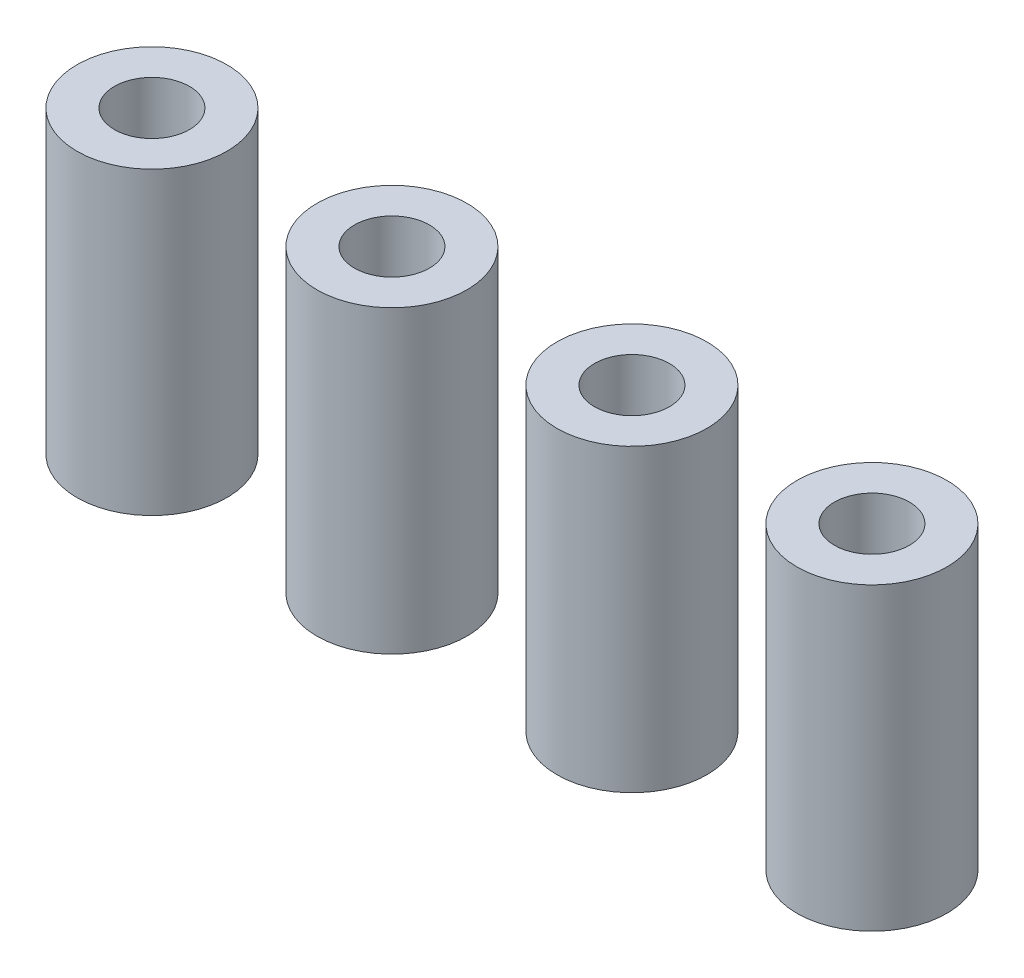
SolidWorks part; units mm, degrees
ref_plane "Front Plane" through (0, 0, 0) normal (0, 0, 1) x (1, 0, 0)
ref_plane "Top Plane" through (0, 0, 0) normal (0, 1, 0) x (1, 0, 0)
ref_plane "Right Plane" through (0, 0, 0) normal (1, 0, 0) x (0, 0, -1)
sketch "Sketch1" plane through (0, 0, 0) normal (0, 1, 0) x (1, 0, 0)
  circle A0 centre (0, 0) radius 2.5
  circle A1 centre (0, 0) radius 1.25
  circle A2 centre (8, 0) radius 2.5
  circle A3 centre (8, 0) radius 1.25
  circle A4 centre (16, 0) radius 2.5
  circle A5 centre (16, 0) radius 1.25
  circle A6 centre (24, 0) radius 2.5
  circle A7 centre (24, 0) radius 1.25
  dimension "D1" = 2.5
  dimension "D2" = 5
  dimension "D3" = 4
extrude "Boss-Extrude1" add sketch "Sketch1" along normal blind 10
